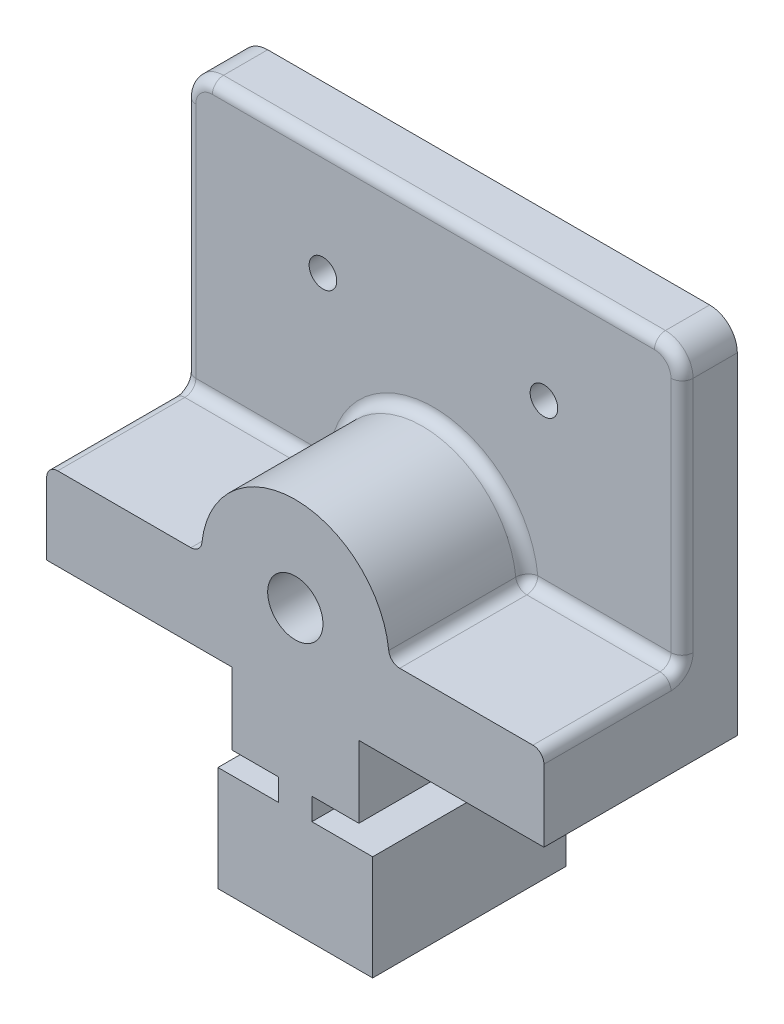
SolidWorks part; units mm, degrees
material "铸造碳钢"
ref_plane "前视基准面" through (0, 0, 0) normal (0, 0, 1) x (1, 0, 0)
ref_plane "上视基准面" through (0, 0, 0) normal (0, 1, 0) x (1, 0, 0)
ref_plane "右视基准面" through (0, 0, 0) normal (1, 0, 0) x (0, 0, -1)
sketch "草图2" plane through (0, 0, 0) normal (0, 0, 1) x (1, 0, 0)
  line L0 (-45, 0) -> (45, 0) construction
  line L1 (-45, 50) -> (45, 50)
  line L2 (-45, 50) -> (-45, -51)
  line L3 (-45, -51) -> (45, -51)
  line L4 (45, 50) -> (45, -51)
  dimension "D1" = 50
  dimension "D2" = 101
  dimension "D3" = 90
extrude "凸台-拉伸1" add sketch "草图2" along normal blind 35
sketch "草图3" plane through (0, 0, 0) normal (0, 0, 1) x (1, 0, 0)
  line L0 (45, 50) -> (-45, 50) construction
  line L1 (45, -51) -> (45, 50) construction
  line L2 (-45, 50) -> (-45, -51) construction
  line L3 (45, 50) -> (-45, 50)
  line L4 (45, 0) -> (45, 50)
  line L5 (-45, 50) -> (-45, 0)
  line L6 (-45, 0) -> (-17, 0)
  line L7 (17, 0) -> (45, 0)
  arc A0 (17, 0) -> (-17, 0) centre (0, 0) ccw
  dimension "D1" = 17
extrude "切除-拉伸1" cut sketch "草图3" along normal through all from offset 10
sketch "草图8" plane through (0, 0, 35) normal (0, 0, 1) x (1, 0, 0)
  line L0 (-45, -15) -> (-11.5, -15)
  line L1 (-45, 0) -> (-45, -51) construction
  line L2 (-11.5, -15) -> (-11.5, -28)
  line L3 (-11.5, -28) -> (-3, -28)
  line L4 (-3, -28) -> (-3, -32)
  line L5 (-3, -32) -> (-14, -32)
  line L6 (-14, -32) -> (-14, -51)
  line L7 (-45, -51) -> (45, -51) construction
  line L8 (-14, -51) -> (-45, -51)
  line L9 (-45, -51) -> (-45, -15)
  line L10 (45, 50) -> (-45, 50) construction
  line L11 (0, 0) -> (0, -51) construction
  line L12 (45, -51) -> (45, -15)
  line L13 (14, -51) -> (45, -51)
  line L14 (14, -32) -> (14, -51)
  line L15 (3, -32) -> (14, -32)
  line L16 (3, -28) -> (3, -32)
  line L17 (11.5, -28) -> (3, -28)
  line L18 (11.5, -15) -> (11.5, -28)
  line L19 (45, -15) -> (11.5, -15)
  circle A0 centre (0, 0) radius 5
  dimension "D7" = 10
  dimension "D1" = 65
  dimension "D2" = 23
  dimension "D3" = 19
  dimension "D4" = 6
  dimension "D5" = 28
  dimension "D6" = 23
extrude "切除-拉伸3" cut sketch "草图8" against normal through all
sketch "草图9" plane through (0, 0, 0) normal (0, 0, -1) x (-1, 0, 0)
  line L0 (11.5, -28) -> (11.5, -15) construction
  line L1 (-11.5, -15) -> (11.5, -15)
  line L2 (-11.5, -15) -> (-11.5, -19)
  line L3 (-11.5, -19) -> (11.5, -19)
  line L4 (11.5, -15) -> (11.5, -19)
  dimension "D1" = 4
extrude "切除-拉伸4" cut sketch "草图9" against normal up to surface (10 mm away) up to face at (0, 19.5, 10)
hole_wizard "M5 螺纹孔1" positions "草图11" profile "草图10" tap size "M5" standard "GB" end condition through all
sketch "草图11" plane through (0, 0, 10) normal (0, 0, 1) x (1, 0, 0)
  line L0 (45, 50) -> (-45, 50) construction
  line L1 (0, 64.574) -> (0, 0) construction
  point P0 (-20, 30)
  point P6 (20, 30)
  dimension "D1" = 20
  dimension "D2" = 40
sketch "草图10" plane through (-20, 30, 10) normal (1, 0, 0) x (0, -1, 0)
  line L0 (0, 0) -> (0, 10)
  line L1 (0, 10) -> (2.5, 10)
  line L2 (2.5, 10) -> (2.5, 0)
  line L5 (2.5, 0) -> (0, 0)
  line L11 (0, -6.35) -> (0, 107.95) construction
  dimension "螺纹线主直径" = 5
  dimension "通孔螺纹孔钻头深度" = 10
sketch "草图12" plane through (0, 0, 0) normal (0, 0, -1) x (-1, 0, 0)
  circle A0 centre (0, 0) radius 8
  dimension "D1" = 16
extrude "切除-拉伸5" cut sketch "草图12" against normal blind 5
fillet "圆角3" radius 5 2 edges at (45, 50, 5) (-45, 50, 5)
fillet "圆角4" radius 2 12 edges at (45, 22.5, 10) (43.5355, 48.5355, 10) (0, 50, 10) (-43.5355, 48.5355, 10) (45, 0, 22.5) (31, 0, 10) (17, 0, 22.5) (0, 17, 10) (-31, 0, 10) (-17, 0, 22.5) (-45, 0, 22.5) (-45, 22.5, 10)
